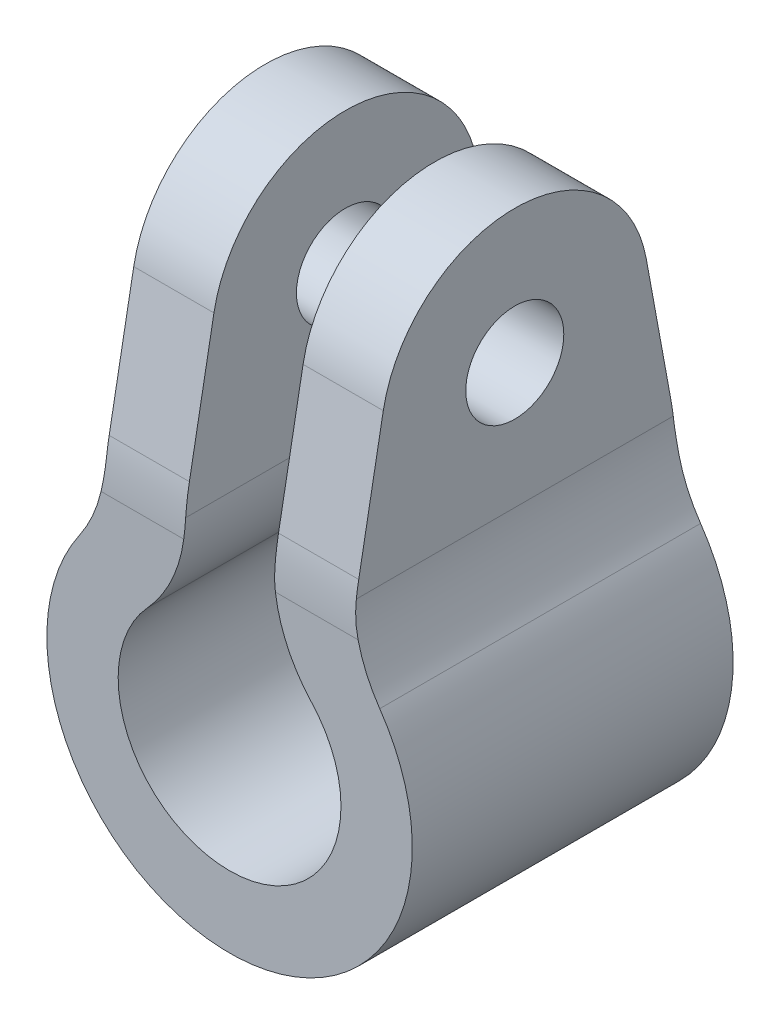
SolidWorks part; units mm, degrees
ref_plane "Front Plane" through (0, 0, 0) normal (0, 0, 1) x (1, 0, 0)
ref_plane "Top Plane" through (0, 0, 0) normal (0, 1, 0) x (1, 0, 0)
ref_plane "Right Plane" through (0, 0, 0) normal (1, 0, 0) x (0, 0, -1)
sketch "Sketch1" plane through (0, 0, 0) normal (0, 0, 1) x (1, 0, 0)
  line L0 (-2.5, 9.9404) -> (-2.5, 5.7282)
  line L1 (2.5, 9.9404) -> (2.5, 5.7282)
  arc A0 (-2.5, 5.7282) -> (2.5, 5.7282) centre (0, 0) ccw
  arc A1 (-2.5, 9.9404) -> (2.5, 9.9404) centre (0, 0) ccw
  arc A2 (2.5, 5.7282) -> (-2.5, 5.7282) centre (0, 0) ccw construction
  arc A3 (2.5, 9.9404) -> (-2.5, 9.9404) centre (0, 0) ccw construction
  dimension "D1" = 12.5
  dimension "D2" = 4
  dimension "D3" = 5
extrude "Boss-Extrude1" add sketch "Sketch1" along normal mid plane 18
sketch "Sketch2" plane through (0, 0, 0) normal (1, 0, 0) x (0, 0, -1)
  line L0 (-9, 9.9404) -> (-7.377, 18.7929)
  line L2 (-9, 9.9404) -> (9, 9.9404) construction
  line L3 (9, 9.9404) -> (7.377, 18.7929)
  line L4 (0, 9.9404) -> (9, 9.9404) construction
  line L5 (9, -10.25) -> (9, 9.9404) construction
  line L6 (0, 9.9404) -> (9, 9.9404) construction
  line L7 (-9, 9.9404) -> (-9, -0.1548)
  line L8 (-9, -0.1548) -> (9, -0.1548)
  line L9 (9, 9.9404) -> (9, -0.1548)
  line L10 (-9, 9.9404) -> (0, 9.9404) construction
  line L11 (-9, 9.9404) -> (0, 9.9404) construction
  line L12 (-9, 9.9404) -> (-9, -10.25) construction
  arc A0 (7.377, 18.7929) -> (-7.377, 18.7929) centre (0, 17.4404) ccw
  circle A1 centre (0, 17.4404) radius 2.75
  arc A2 (-7.377, 18.7929) -> (0, 9.9404) centre (0, 17.4404) ccw construction
  arc A3 (0, 9.9404) -> (7.377, 18.7929) centre (0, 17.4404) ccw construction
  point P15 (-9, -0.163)
  dimension "D1" = 15
  dimension "D2" = 5.5
extrude "Boss-Extrude2" add sketch "Sketch2" along normal mid plane 14
sketch "Sketch3" plane through (0, 0, 9) normal (0, 0, 1) x (1, 0, 0)
  line L0 (-2.5, 9.9404) -> (-2.5, 24.9404)
  line L1 (7, 24.9404) -> (-7, 24.9404) construction
  line L2 (-2.5, 5.7282) -> (-2.5, 9.9404)
  line L3 (2.5, 9.9404) -> (2.5, 5.7282)
  line L4 (-2.5, 5.7282) -> (-2.5, 9.9404)
  line L5 (2.5, 9.9404) -> (2.5, 5.7282)
  line L6 (-2.5, 24.9404) -> (2.5, 24.9404)
  line L7 (2.5, 24.9404) -> (2.5, 9.9404)
  arc A2 (-2.5, 5.7282) -> (2.5, 5.7282) centre (0, 0) ccw
  arc A3 (-2.5, 9.9404) -> (2.5, 9.9404) centre (0, 0) ccw
  arc A4 (-2.5, 5.7282) -> (2.5, 5.7282) centre (0, 0) ccw
  arc A5 (-2.5, 9.9404) -> (2.5, 9.9404) centre (0, 0) ccw construction
  dimension "D1" = 0
extrude "Cut-Extrude1" cut sketch "Sketch3" against normal through all both and the other way through all
fillet "Fillet1" radius 8 4 edges at (-7, 7.4875, 0) (7, 7.4875, 0)
fillet "Fillet2" radius 15 4 edges at (-4.7565, 9.9404, 9) (4.7565, 9.9404, 9) (4.7565, 9.9404, -9) (-4.7565, 9.9404, -9)
